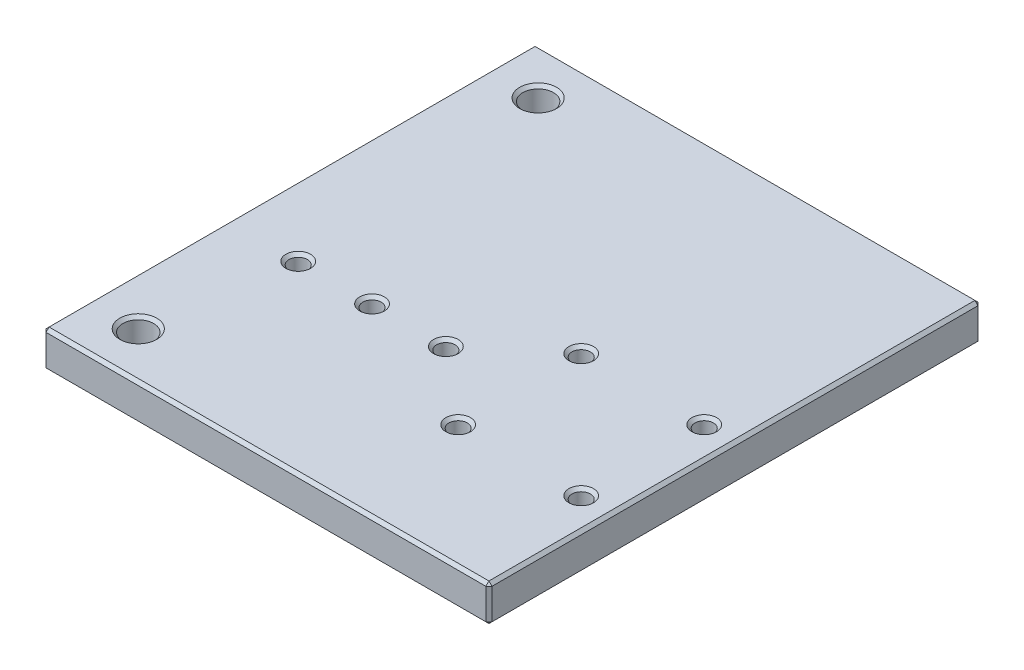
SolidWorks part; units mm, degrees
ref_plane "Alzado" through (0, 0, 0) normal (0, 0, 1) x (1, 0, 0)
ref_plane "Planta" through (0, 0, 0) normal (0, 1, 0) x (1, 0, 0)
ref_plane "Vista lateral" through (0, 0, 0) normal (1, 0, 0) x (0, 0, -1)
sketch "Croquis1" plane through (0, 0, 0) normal (0, 1, 0) x (1, 0, 0)
  line L1 (-30.519, 26.2785) -> (41.981, 26.2785)
  line L2 (-30.519, 26.2785) -> (-30.519, -53.7215)
  line L3 (-30.519, -53.7215) -> (41.981, -53.7215)
  line L4 (41.981, 26.2785) -> (41.981, -53.7215)
  circle A0 centre (16.981, -13.7215) radius 1.5
  circle A1 centre (36.981, -13.7215) radius 1.5
  circle A2 centre (16.981, -33.7215) radius 1.5
  circle A3 centre (36.981, -33.7215) radius 1.5
  circle A4 centre (-7.019, -23.7215) radius 1.5
  circle A5 centre (4.981, -23.7215) radius 1.5
  circle A6 centre (-22.519, 18.7785) radius 2.5
  circle A7 centre (-22.519, -46.2215) radius 2.5
  circle A8 centre (-19.019, -23.7215) radius 1.5
  dimension "D7" = 3
  dimension "D8" = 3
  dimension "D9" = 3
  dimension "D10" = 3
  dimension "D11" = 3
  dimension "D12" = 3
  dimension "D2" = 5
  dimension "D17" = 5
  dimension "D14" = 3
  dimension "D1" = 80
  dimension "D3" = 20
  dimension "D4" = 20
  dimension "D5" = 40
  dimension "D6" = 5
  dimension "D13" = 12
  dimension "D15" = 50
  dimension "D16" = 12
  dimension "D18" = 64.5
  dimension "D19" = 7.5
  dimension "D20" = 7.5
  dimension "D21" = 12
extrude "Saliente-Extruir1" add sketch "Croquis1" along normal blind 6
chamfer "Chaflán1" distance 0.5 angle 45 30 edges at (36.981, 0, 35.2215) (36.981, 0, 15.2215) (16.981, 0, 15.2215) (16.981, 0, 35.2215) (36.981, 6, 35.2215) (36.981, 6, 15.2215) (-30.519, 3, -26.2785) (-30.519, 3, 53.7215) (41.981, 3, 53.7215) (5.731, 0, 53.7215) (41.981, 0, 13.7215) (-30.519, 0, 13.7215) (5.731, 0, -26.2785) (41.981, 3, -26.2785) (5.731, 6, -26.2785) (41.981, 6, 13.7215) (5.731, 6, 53.7215) (-30.519, 6, 13.7215) (16.981, 6, 15.2215) (16.981, 6, 35.2215) (4.981, 0, 25.2215) (-7.019, 0, 25.2215) (4.981, 6, 25.2215) (-7.019, 6, 25.2215) (-22.519, 0, 48.7215) (-22.519, 0, -16.2785) (-22.519, 6, 48.7215) (-22.519, 6, -16.2785) (-19.019, 0, 25.2215) (-19.019, 6, 25.2215)
